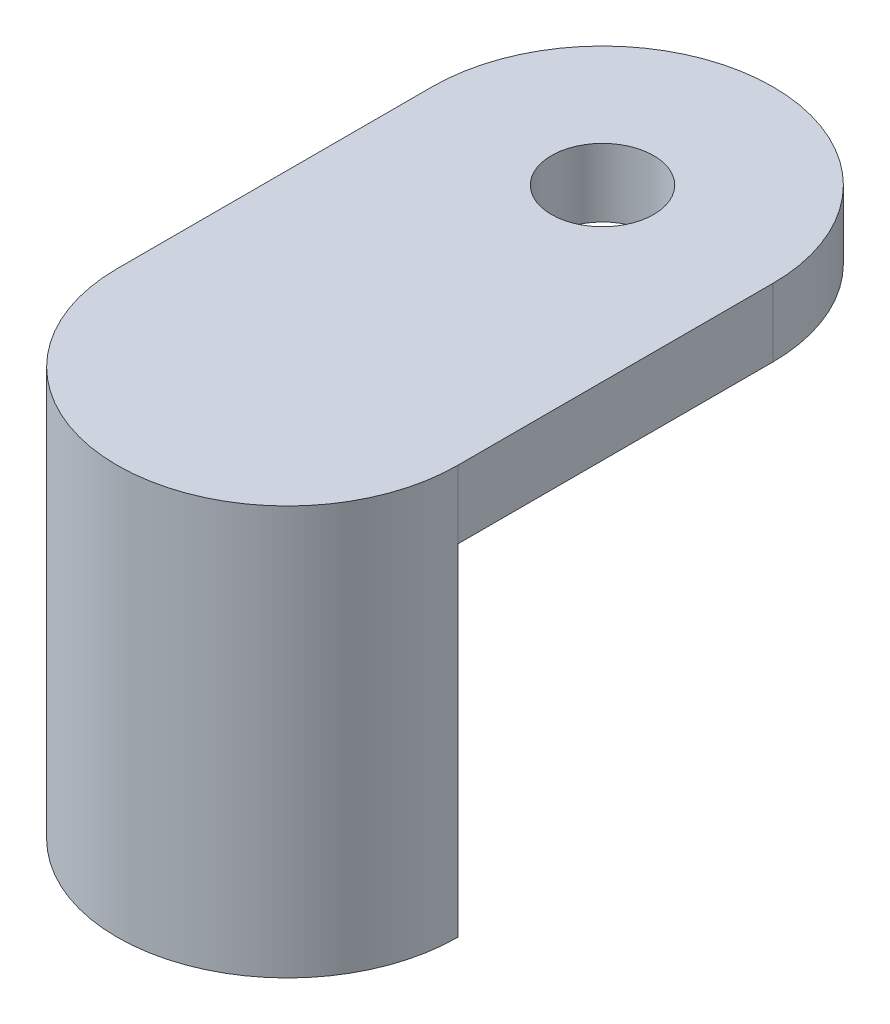
SolidWorks part; units mm, degrees
ref_plane "前视基准面" through (0, 0, 0) normal (0, 0, 1) x (1, 0, 0)
ref_plane "上视基准面" through (0, 0, 0) normal (0, 1, 0) x (1, 0, 0)
ref_plane "右视基准面" through (0, 0, 0) normal (1, 0, 0) x (0, 0, -1)
other "Configuration Table"
sketch "草图1" plane through (0, 0, 0) normal (0, 1, 0) x (1, 0, 0)
  line L2 (-5, 0) -> (-5, -9.25)
  line L3 (5, 0) -> (5, -9.25)
  arc A0 (5, 0) -> (-5, 0) centre (0, 0) ccw
  arc A2 (-5, -9.25) -> (5, -9.25) centre (0, -9.25) ccw
  point P6 (0, 0)
  dimension "D1" = 10
  dimension "D2" = 10
  dimension "D3" = 9.25
extrude "凸台-拉伸1" add sketch "草图1" along normal blind 2
sketch "草图2" plane through (0, 2, 0) normal (0, 1, 0) x (1, 0, 0)
  circle A0 centre (0, 0) radius 1.5
  dimension "D1" = 3
extrude "切除-拉伸1" cut sketch "草图2" against normal blind 2
sketch "草图3" plane through (0, 2, 0) normal (0, 1, 0) x (1, 0, 0)
  line L0 (-5, -9.25) -> (5, -9.25)
  arc A0 (-5, -9.25) -> (5, -9.25) centre (0, -9.25) ccw construction
  arc A1 (-5, -9.25) -> (5, -9.25) centre (0, -9.25) ccw
extrude "凸台-拉伸2" add sketch "草图3" against normal blind 12
